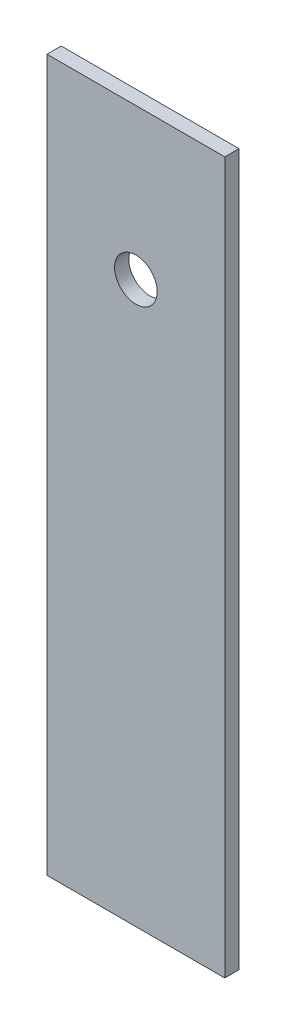
SolidWorks part; units mm, degrees
ref_plane "正面" through (0, 0, 0) normal (0, 0, 1) x (1, 0, 0)
ref_plane "平面" through (0, 0, 0) normal (0, 1, 0) x (1, 0, 0)
ref_plane "右側面" through (0, 0, 0) normal (1, 0, 0) x (0, 0, -1)
sketch "ｽｹｯﾁ1" plane through (0, 0, 0) normal (0, 0, 1) x (1, 0, 0)
  line L0 (0, 50) -> (0, -50) construction
  line L1 (-12.5, 50) -> (12.5, 50)
  line L2 (-12.5, 50) -> (-12.5, -50)
  line L3 (-12.5, -50) -> (12.5, -50)
  line L4 (12.5, 50) -> (12.5, -50)
  line L5 (-12.5, 50) -> (12.5, -50) construction
  line L6 (-12.5, -50) -> (12.5, 50) construction
  circle A0 centre (0, 28.8) radius 3
  point P0 (0, 0)
  dimension "D3" = 6
  dimension "D1" = 100
  dimension "D2" = 25
  dimension "D4" = 78.8
extrude "ﾎﾞｽ - 押し出し1" add sketch "ｽｹｯﾁ1" along normal blind 2
